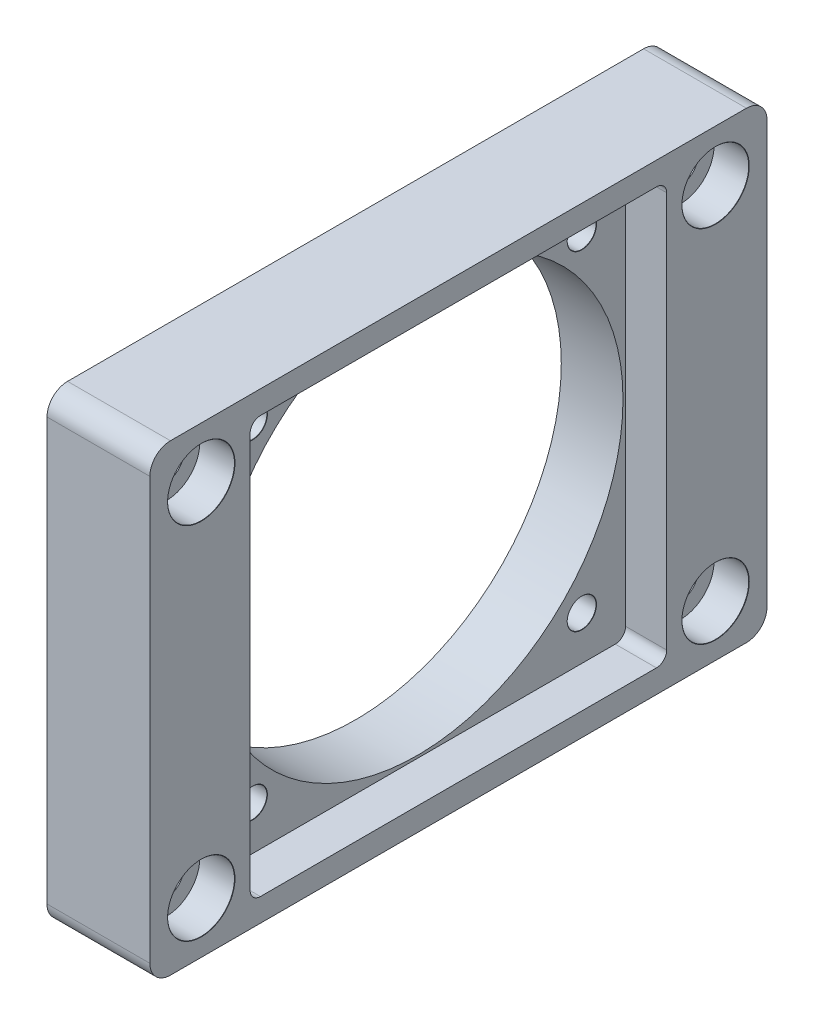
SolidWorks part; units mm, degrees
ref_plane "Front Plane" through (0, 0, 0) normal (0, 0, 1) x (1, 0, 0)
ref_plane "Top Plane" through (0, 0, 0) normal (0, 1, 0) x (1, 0, 0)
ref_plane "Right Plane" through (0, 0, 0) normal (1, 0, 0) x (0, 0, -1)
sketch "Sketch1" plane through (0, 0, 0) normal (1, 0, 0) x (0, 0, -1)
  line L1 (-30, 22.5) -> (30, 22.5)
  line L2 (-30, 22.5) -> (-30, -22.5)
  line L3 (-30, -22.5) -> (30, -22.5)
  line L4 (30, 22.5) -> (30, -22.5)
  line L5 (-30, 22.5) -> (30, -22.5) construction
  line L6 (-30, -22.5) -> (30, 22.5) construction
  point P0 (0, 0)
  dimension "D1" = 60
  dimension "D2" = 45
extrude "Boss-Extrude1" add sketch "Sketch1" along normal blind 10
sketch "Sketch2" plane through (10, 0, 0) normal (1, 0, 0) x (0, 0, -1)
  line L1 (-20.25, 20.25) -> (20.25, 20.25)
  line L2 (-20.25, 20.25) -> (-20.25, -20.25)
  line L3 (-20.25, -20.25) -> (20.25, -20.25)
  line L4 (20.25, 20.25) -> (20.25, -20.25)
  line L5 (-20.25, 20.25) -> (20.25, -20.25) construction
  line L6 (-20.25, -20.25) -> (20.25, 20.25) construction
  dimension "D1" = 40.5
extrude "Cut-Extrude1" cut sketch "Sketch2" against normal blind 4
sketch "Sketch3" plane through (6, 0, 0) normal (1, 0, 0) x (0, 0, -1)
  line L0 (-20.25, 20.25) -> (20.25, -20.25) construction
  circle A0 centre (0, 0) radius 20
extrude "Cut-Extrude2" cut sketch "Sketch3" against normal blind 10
fillet "Fillet1" radius 1 4 edges at (8, 20.25, 20.25) (8, 20.25, -20.25) (8, -20.25, -20.25) (8, -20.25, 20.25)
hole_wizard "Ø2.8 (2.8) Diameter Hole1" positions "Sketch11" profile "Sketch12" hole size "Ø2.8" standard "ISO" end condition through all
sketch "Sketch11" plane through (6, 0, 0) normal (1, 0, 0) x (0, 0, -1)
  line L1 (-16, 16) -> (16, 16)
  line L2 (-16, 16) -> (-16, -16)
  line L3 (-16, -16) -> (16, -16)
  line L4 (16, 16) -> (16, -16)
  line L5 (-16, 16) -> (16, -16) construction
  line L6 (-16, -16) -> (16, 16) construction
  point P1 (0, 0)
  point P2 (16, -16)
  point P65 (-16, 16)
  point P66 (-16, -16)
  point P67 (16, 16)
  dimension "D1" = 32
sketch "Sketch12" plane through (6, 0, 0) normal (0, 1, 0) x (0, 0, -1)
  line L0 (0, 0) -> (0, 6)
  line L1 (0, 6) -> (1.4, 6)
  line L2 (1.4, 6) -> (1.4, 0.025)
  line L3 (1.4, 0.025) -> (1.425, 0)
  line L5 (1.425, 0) -> (0, 0)
  line L6 (-1.4, 0.025) -> (-1.425, 0) construction
  line L11 (0, -6.35) -> (0, 107.95) construction
  dimension "Thru Hole Dia." = 2.8
  dimension "Thru Hole Depth" = 6
  dimension "Near C'Sink Dia." = 2.85
  dimension "Near C'Sink Angle" = 90
hole_wizard "CBORE for M3 Hex Socket Head Cap Screw2" positions "Sketch13" profile "Sketch14" counterbore size "M3" standard "ISO" end condition through all
sketch "Sketch13" plane through (10, 0, 0) normal (1, 0, 0) x (0, 0, -1)
  line L1 (-25, 17.5) -> (25, 17.5)
  line L2 (-25, 17.5) -> (-25, -17.5)
  line L3 (-25, -17.5) -> (25, -17.5)
  line L4 (25, 17.5) -> (25, -17.5)
  line L5 (-25, 17.5) -> (25, -17.5) construction
  line L6 (-25, -17.5) -> (25, 17.5) construction
  point P4 (25, -17.5)
  point P9 (0, 0)
  point P77 (-25, 17.5)
  point P78 (-25, -17.5)
  point P79 (25, 17.5)
  dimension "D1" = 50
  dimension "D2" = 35
sketch "Sketch14" plane through (10, -17.5, -25) normal (0, 1, 0) x (0, 0, -1)
  line L0 (0, 0) -> (0, 10)
  line L1 (0, 10) -> (1.7, 10)
  line L3 (1.7, 10) -> (1.7, 3.4)
  line L4 (3.25, 3.4) -> (1.7, 3.4)
  line L5 (3.25, 3.4) -> (3.25, 0.025)
  line L6 (3.25, 0.025) -> (3.275, 0)
  line L7 (3.275, 0) -> (0, 0)
  line L8 (-3.25, 0.025) -> (-3.275, 0) construction
  line L11 (0, -6.35) -> (0, 107.95) construction
  dimension "Thru Hole Dia." = 3.4
  dimension "Thru Hole Depth" = 10
  dimension "C'Bore Dia." = 6.5
  dimension "C'Bore Depth" = 3.4
  dimension "Near C'Sink Dia." = 6.55
  dimension "Near C'Sink Angle" = 90
fillet "Fillet3" radius 2 4 edges at (5, 22.5, -30) (5, -22.5, -30) (5, 22.5, 30) (5, -22.5, 30)
